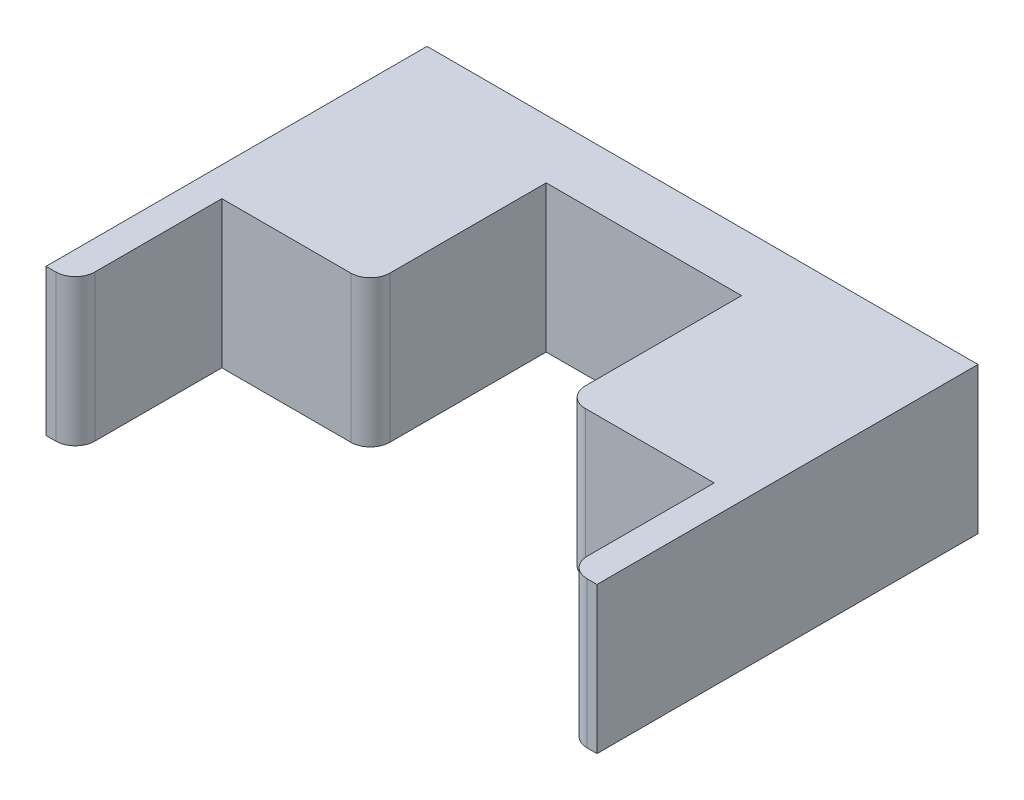
SolidWorks part; units mm, degrees
ref_plane "Front Plane" through (0, 0, 0) normal (0, 0, 1) x (1, 0, 0)
ref_plane "Top Plane" through (0, 0, 0) normal (0, 1, 0) x (1, 0, 0)
ref_plane "Right Plane" through (0, 0, 0) normal (1, 0, 0) x (0, 0, -1)
sketch "Sketch1" plane through (0, 0, 0) normal (0, 1, 0) x (1, 0, 0)
  line L0 (26.9493, 0.1297) -> (29.9493, 0.1297)
  line L9 (-26.4507, 39.1297) -> (29.9493, 39.1297)
  line L10 (-26.4507, 39.1297) -> (-26.4507, 0.1297)
  line L11 (-26.4507, 0.1297) -> (-23.4507, 0.1297)
  line L12 (29.9493, 39.1297) -> (29.9493, 0.1297)
  line L14 (-23.4507, 0.1297) -> (-23.4507, 15.1297)
  line L15 (-23.4507, 15.1297) -> (-8.2507, 15.1297)
  line L16 (26.9493, 0.1297) -> (26.9493, 15.1297)
  line L17 (11.7493, 15.1297) -> (26.9493, 15.1297)
  line L19 (-8.2507, 15.1297) -> (-8.2507, 33.1297)
  line L20 (-8.2507, 33.1297) -> (11.7493, 33.1297)
  line L21 (11.7493, 15.1297) -> (11.7493, 33.1297)
  dimension "D1" = 50.4
  dimension "D2" = 15
  dimension "D3" = 3
  dimension "D4" = 3
  dimension "D5" = 20
  dimension "D6" = 18
  dimension "D7" = 39
  dimension "D8" = 18.2
extrude "Boss-Extrude1" add sketch "Sketch1" along normal blind 15
fillet "Fillet2" radius 2 4 edges at (26.9493, 7.5, -0.1297) (11.7493, 7.5, -15.1297) (-8.2507, 7.5, -15.1297) (-23.4507, 7.5, -0.1297)
equation "\"steelwidth\"=50.4"
equation "\"D1@Sketch1\"=\"steelwidth\""
equation "\"railwidth\"=20"
equation "\"D5@Sketch1\"=\"railwidth\""
equation "\"railheight\"=18"
equation "\"D6@Sketch1\"=\"railheight\""
equation "\"D7@Sketch1\"=\"railheight\"+15+6"
equation "\"D8@Sketch1\"=(\"steelwidth\"+6-\"railwidth\")/2"
